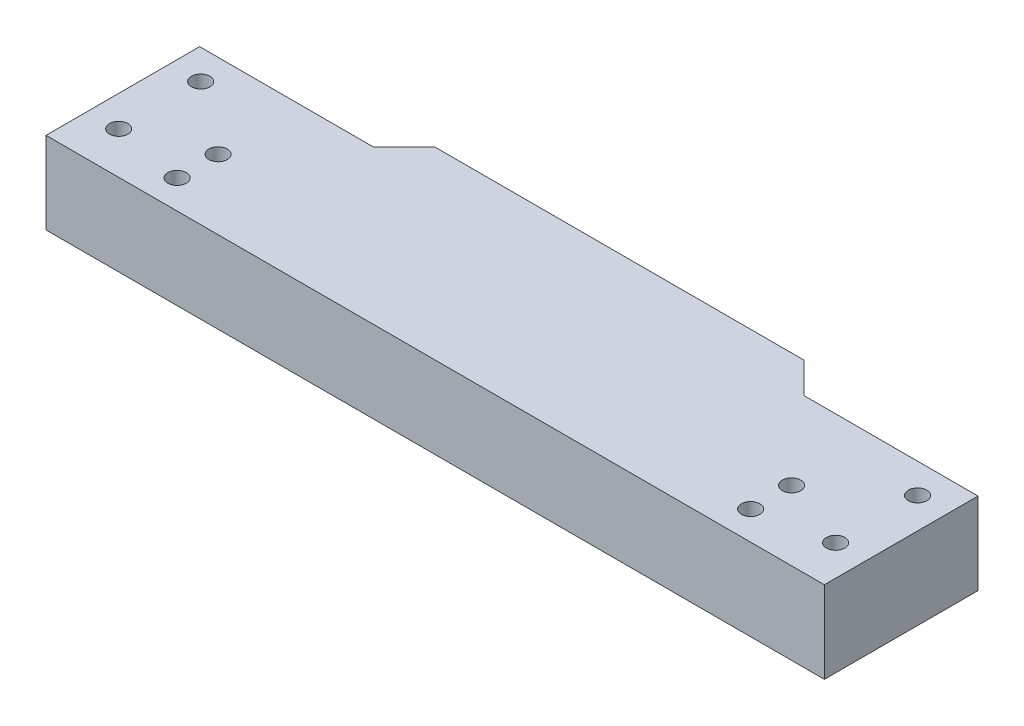
SolidWorks part; units mm, degrees
ref_plane "Plan de face" through (0, 0, 0) normal (0, 0, 1) x (1, 0, 0)
ref_plane "Plan de dessus" through (0, 0, 0) normal (0, 1, 0) x (1, 0, 0)
ref_plane "Plan de droite" through (0, 0, 0) normal (1, 0, 0) x (0, 0, -1)
sketch "Esquisse1" plane through (0, 0, 0) normal (0, 1, 0) x (1, 0, 0)
  line L0 (-190, 0) -> (190, 0)
  line L1 (190, 0) -> (190, 75)
  line L2 (190, 75) -> (105, 75)
  line L3 (105, 75) -> (90, 90)
  line L4 (90, 90) -> (-90, 90)
  line L5 (0, 90) -> (0, 0)
  line L6 (105, 75) -> (55.7702, 75) construction
  line L7 (-105, 75) -> (-55.7702, 75) construction
  line L8 (-105, 75) -> (-90, 90)
  line L9 (-190, 75) -> (-105, 75)
  line L10 (-190, 0) -> (-190, 75)
  circle A0 centre (140, 14) radius 4.5
  circle A1 centre (140, 34) radius 4.5
  circle A2 centre (175, 20.5) radius 4.5
  circle A3 centre (175, 60.5) radius 4.5
  circle A4 centre (-175, 60.5) radius 4.5
  circle A5 centre (-175, 20.5) radius 4.5
  circle A6 centre (-140, 34) radius 4.5
  circle A7 centre (-140, 14) radius 4.5
  dimension "D6" = 9
  dimension "D9" = 9
  dimension "D12" = 9
  dimension "D14" = 9
  dimension "D11" = 140
  dimension "D1" = 190
  dimension "D2" = 75
  dimension "D3" = 85
  dimension "D4" = 45
  dimension "D5" = 90
  dimension "D7" = 14
  dimension "D8" = 140
  dimension "D10" = 20
  dimension "D13" = 20.5
  dimension "D15" = 15
  dimension "D16" = 40
  dimension "D17" = 15
extrude "Boss.-Extru.1" add sketch "Esquisse1" along normal blind 40 contours L10 L0 L5 L4 L8 L9 A6 A4 A5 A7 | L4 L5 L0 L1 L2 L3 A3 A2 A1 A0
